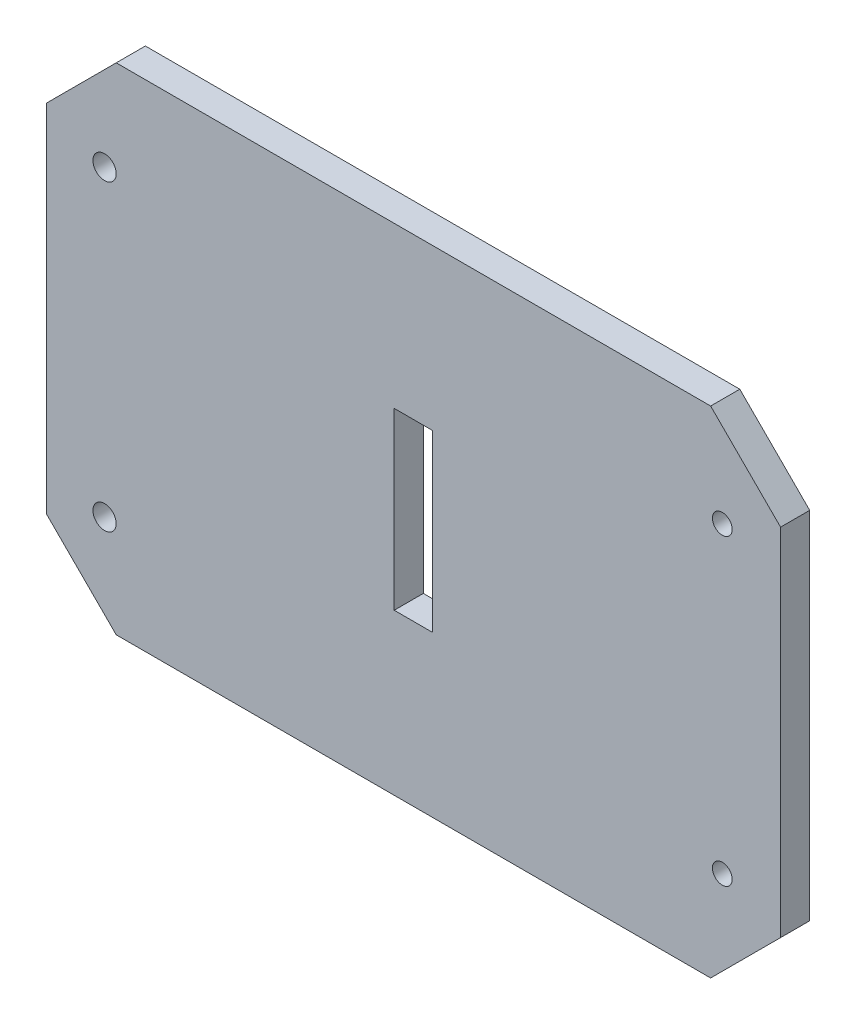
SolidWorks part; units mm, degrees
ref_plane "Спереди" through (0, 0, 0) normal (0, 0, 1) x (1, 0, 0)
ref_plane "Сверху" through (0, 0, 0) normal (0, 1, 0) x (1, 0, 0)
ref_plane "Справа" through (0, 0, 0) normal (1, 0, 0) x (0, 0, -1)
other "Configuration Table"
sketch "Эскиз1" plane through (0, 0, 0) normal (0, 0, 1) x (1, 0, 0)
  line L0 (-51, -42.5) -> (51, -42.5)
  line L1 (51, -42.5) -> (63, -30.5)
  line L2 (63, -30.5) -> (63, 30.5)
  line L3 (63, 30.5) -> (51, 42.5)
  line L4 (51, 42.5) -> (-51, 42.5)
  line L5 (-51, 42.5) -> (-63, 30.5)
  line L6 (-63, 30.5) -> (-63, -30.5)
  line L7 (-63, -30.5) -> (-51, -42.5)
  line L9 (-3.3, -15) -> (3.3, -15)
  line L10 (-3.3, -15) -> (-3.3, 15)
  line L11 (-3.3, 15) -> (3.3, 15)
  line L12 (3.3, -15) -> (3.3, 15)
  circle A0 centre (-53, -26) radius 2
  circle A1 centre (-53, 26) radius 2
  circle A2 centre (53, -26) radius 1.7
  circle A3 centre (53, 26) radius 1.7
extrude "09_C920_tripod_tray" add sketch "Эскиз1" along normal blind 5
